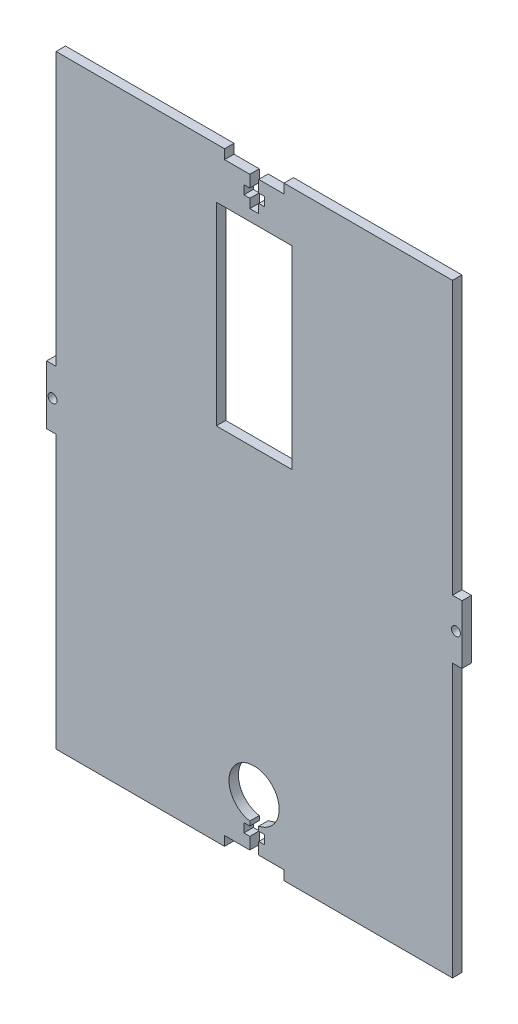
SolidWorks part; units mm, degrees
ref_plane "Front Plane" through (0, 0, 0) normal (0, 0, 1) x (1, 0, 0)
ref_plane "Top Plane" through (0, 0, 0) normal (0, 1, 0) x (1, 0, 0)
ref_plane "Right Plane" through (0, 0, 0) normal (1, 0, 0) x (0, 0, -1)
sketch "Sketch1" plane through (0, 0, 0) normal (0, 0, 1) x (1, 0, 0)
  line L1 (-69.85, 101.6) -> (69.85, 101.6)
  line L2 (-69.85, 101.6) -> (-69.85, -101.6)
  line L3 (-69.85, -101.6) -> (69.85, -101.6)
  line L4 (69.85, 101.6) -> (69.85, -101.6)
  line L5 (-69.85, 101.6) -> (69.85, -101.6) construction
  line L6 (-69.85, -101.6) -> (69.85, 101.6) construction
  point P0 (0, 0)
  dimension "D1" = 203.2
  dimension "D2" = 139.7
extrude "Boss-Extrude1" add sketch "Sketch1" along normal blind 3.18
sketch "Sketch2" plane through (0, 0, 3.18) normal (0, 0, 1) x (1, 0, 0)
  line L0 (0, 0) -> (69.85, 0) construction
  line L1 (-10, 101.6) -> (10, 101.6)
  line L2 (-10, 101.6) -> (-10, 98.42)
  line L3 (-10, 98.42) -> (-1.5, 98.42)
  line L4 (10, 101.6) -> (10, 98.42)
  line L5 (69.85, -101.6) -> (69.85, 101.6) construction
  line L6 (0, 0) -> (0, 101.6) construction
  line L7 (-1.5, 88.42) -> (1.5, 88.42)
  line L8 (-1.5, 88.42) -> (-1.5, 91.42)
  line L10 (1.5, 88.42) -> (1.5, 91.42)
  line L12 (69.85, 101.6) -> (-69.85, 101.6) construction
  line L13 (3.5, 94.42) -> (1.5, 94.42)
  line L14 (3.5, 94.42) -> (3.5, 91.42)
  line L15 (3.5, 91.42) -> (1.5, 91.42)
  line L16 (-3.5, 94.42) -> (-3.5, 91.42)
  line L17 (-10, -101.6) -> (-10, -98.42)
  line L18 (-10, -98.42) -> (-1.5, -98.42)
  line L19 (-1.5, -94.42) -> (-1.5, -98.42)
  line L20 (-1.5, -94.42) -> (-3.5, -94.42)
  line L21 (-3.5, -94.42) -> (-3.5, -91.42)
  line L22 (1.5, 98.42) -> (10, 98.42)
  line L23 (-1.5, 94.42) -> (-3.5, 94.42)
  line L24 (-1.5, -91.42) -> (-3.5, -91.42)
  line L25 (-1.5, -88.42) -> (-1.5, -91.42)
  line L26 (-1.5, -88.42) -> (1.5, -88.42)
  line L27 (-1.5, 91.42) -> (-3.5, 91.42)
  line L28 (1.5, -88.42) -> (1.5, -91.42)
  line L29 (-1.5, 94.42) -> (-1.5, 98.42)
  line L30 (1.5, 94.42) -> (1.5, 98.42)
  line L31 (3.5, -91.42) -> (1.5, -91.42)
  line L32 (3.5, -94.42) -> (3.5, -91.42)
  line L33 (3.5, -94.42) -> (1.5, -94.42)
  line L34 (1.5, -94.42) -> (1.5, -98.42)
  line L35 (1.5, -98.42) -> (10, -98.42)
  line L36 (10, -101.6) -> (10, -98.42)
  line L37 (-10, -101.6) -> (10, -101.6)
  line L38 (-69.85, 101.6) -> (-69.85, -101.6) construction
  line L39 (-69.85, 101.6) -> (-66.67, 101.6)
  line L40 (-69.85, 101.6) -> (-69.85, 9.875)
  line L41 (-69.85, 9.875) -> (-66.67, 9.875)
  line L42 (-66.67, 101.6) -> (-66.67, 9.875)
  line L43 (-69.85, -101.6) -> (-66.67, -101.6)
  line L44 (-69.85, -101.6) -> (-69.85, -9.875)
  line L45 (-69.85, -9.875) -> (-66.67, -9.875)
  line L46 (-66.67, -101.6) -> (-66.67, -9.875)
  line L47 (69.85, -9.875) -> (66.67, -9.875)
  line L48 (66.67, -101.6) -> (66.67, -9.875)
  line L49 (69.85, -101.6) -> (66.67, -101.6)
  line L50 (69.85, -101.6) -> (69.85, -9.875)
  line L51 (69.85, 9.875) -> (66.67, 9.875)
  line L52 (66.67, 101.6) -> (66.67, 9.875)
  line L53 (69.85, 101.6) -> (66.67, 101.6)
  line L54 (69.85, 101.6) -> (69.85, 9.875)
  circle A0 centre (-67.85, 0) radius 1.5
  circle A1 centre (67.85, 0) radius 1.5
  point P0 (0, 50.5662)
  point P5 (0, 32.0079)
  point P10 (15.4931, 34.4893)
  dimension "D11" = 3
  dimension "D12" = 2
  dimension "D1" = 20
  dimension "D2" = 19.75
  dimension "D3" = 4
  dimension "D4" = 3
  dimension "D5" = 3.18
  dimension "D6" = 7
  dimension "D7" = 3
  dimension "D8" = 3
  dimension "D9" = 3.18
  dimension "D10" = 3.18
extrude "Cut-Extrude1" cut sketch "Sketch2" against normal through all
sketch "Sketch3" plane through (0, 0, 0) normal (0, 0, -1) x (-1, 0, 0)
  circle A0 centre (0.0688, -81.6486) radius 8.442
  point P3 (0, -81.6486)
extrude "Cut-Extrude2" cut sketch "Sketch3" against normal blind 10 contours A0
sketch "Sketch5" plane through (0, 0, 0) normal (0, 0, -1) x (-1, 0, 0)
  line L1 (12.7653, 84.6626) -> (-12.7653, 84.6626)
  line L2 (12.7653, 84.6626) -> (12.7653, 19.4862)
  line L3 (12.7653, 19.4862) -> (-12.7653, 19.4862)
  line L4 (-12.7653, 84.6626) -> (-12.7653, 19.4862)
  line L5 (12.7653, 84.6626) -> (-12.7653, 19.4862) construction
  line L6 (12.7653, 19.4862) -> (-12.7653, 84.6626) construction
  point P0 (0, 52.0744)
extrude "Cut-Extrude3" cut sketch "Sketch5" against normal blind 10
